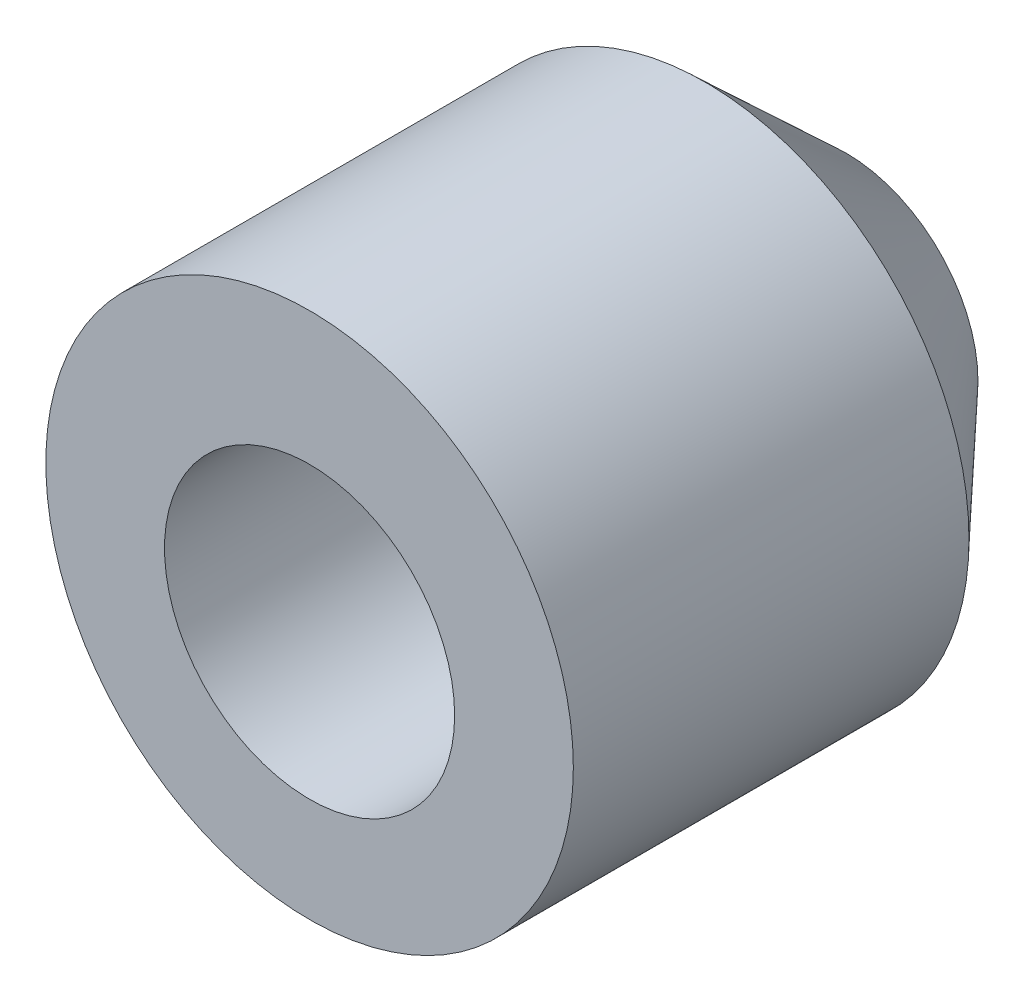
SolidWorks part; units mm, degrees
ref_plane "Front Plane" through (0, 0, 0) normal (0, 0, 1) x (1, 0, 0)
ref_plane "Top Plane" through (0, 0, 0) normal (0, 1, 0) x (1, 0, 0)
ref_plane "Right Plane" through (0, 0, 0) normal (1, 0, 0) x (0, 0, -1)
sketch "Sketch2" plane through (0, 0, 0) normal (1, 0, 0) x (0, 0, -1)
  line L0 (0, -1.8039) -> (0, 8.1961)
  line L1 (0, 8.1961) -> (15, 8.1961)
  line L2 (0, -1.8039) -> (15, -1.8039)
  line L3 (0, 3.1961) -> (29.9389, 3.1961) construction
  line L4 (15, 8.1961) -> (20.3415, 3.1961)
  line L5 (20.3415, 3.1961) -> (15, -1.8039)
  dimension "D1" = 10
  dimension "15" = 15
revolve "Revolve3" add sketch "Sketch2" angle 360 about L1
sketch "Sketch3" plane through (0, 0, 0) normal (0, 0, 1) x (1, 0, 0)
  line L0 (-9.9849, 7.6474) -> (9.9849, 7.6474) construction
  circle A0 centre (0, 7.6474) radius 5.5
  circle A1 centre (0, 8.1961) radius 10 construction
  point P7 (0, 0)
  point P8 (0, 0)
  point P9 (0, 7.6474)
  point P10 (0, 0)
  dimension "D1" = 11
extrude "Cut-Extrude1" cut sketch "Sketch3" against normal blind 10
